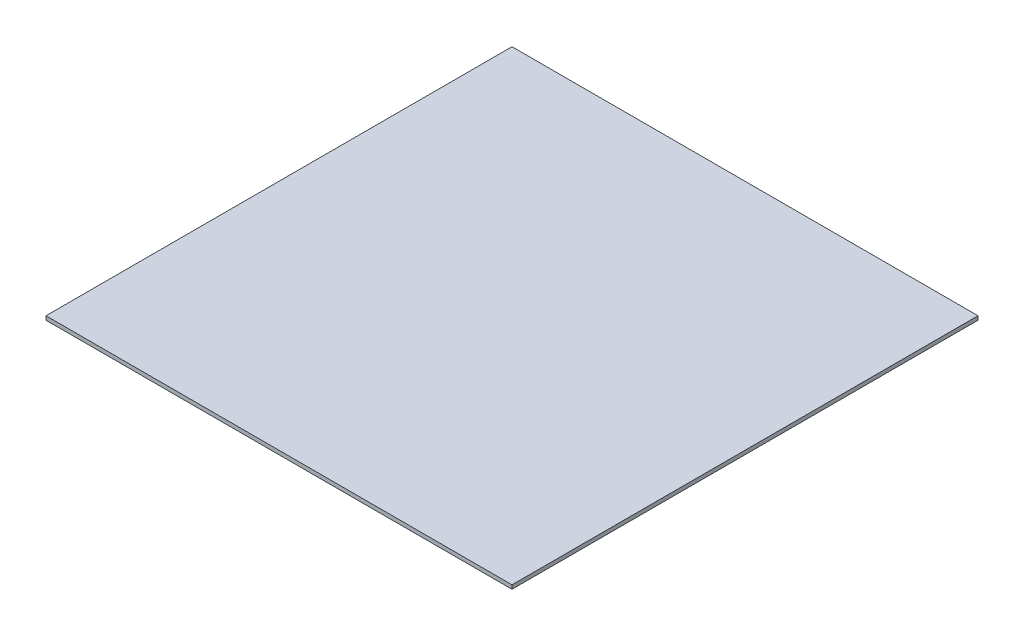
SolidWorks part; units mm, degrees
ref_plane "Front" through (0, 0, 0) normal (0, 0, 1) x (1, 0, 0)
ref_plane "Top" through (0, 0, 0) normal (0, 1, 0) x (1, 0, 0)
ref_plane "Right" through (0, 0, 0) normal (1, 0, 0) x (0, 0, -1)
sketch "Sketch1" plane through (0, 0, 0) normal (0, 1, 0) x (1, 0, 0)
  line L0 (-381, 381) -> (381, -381) construction
  line L1 (-381, 381) -> (381, 381)
  line L2 (-381, 381) -> (-381, -381)
  line L3 (-381, -381) -> (381, -381)
  line L4 (381, 381) -> (381, -381)
  line L5 (-381, -381) -> (381, 381) construction
  dimension "D1" = 762
  dimension "D2" = 762
extrude "Boss-Extrude1" add sketch "Sketch1" along normal blind 6.35 contours L1 L4 L3 L2
